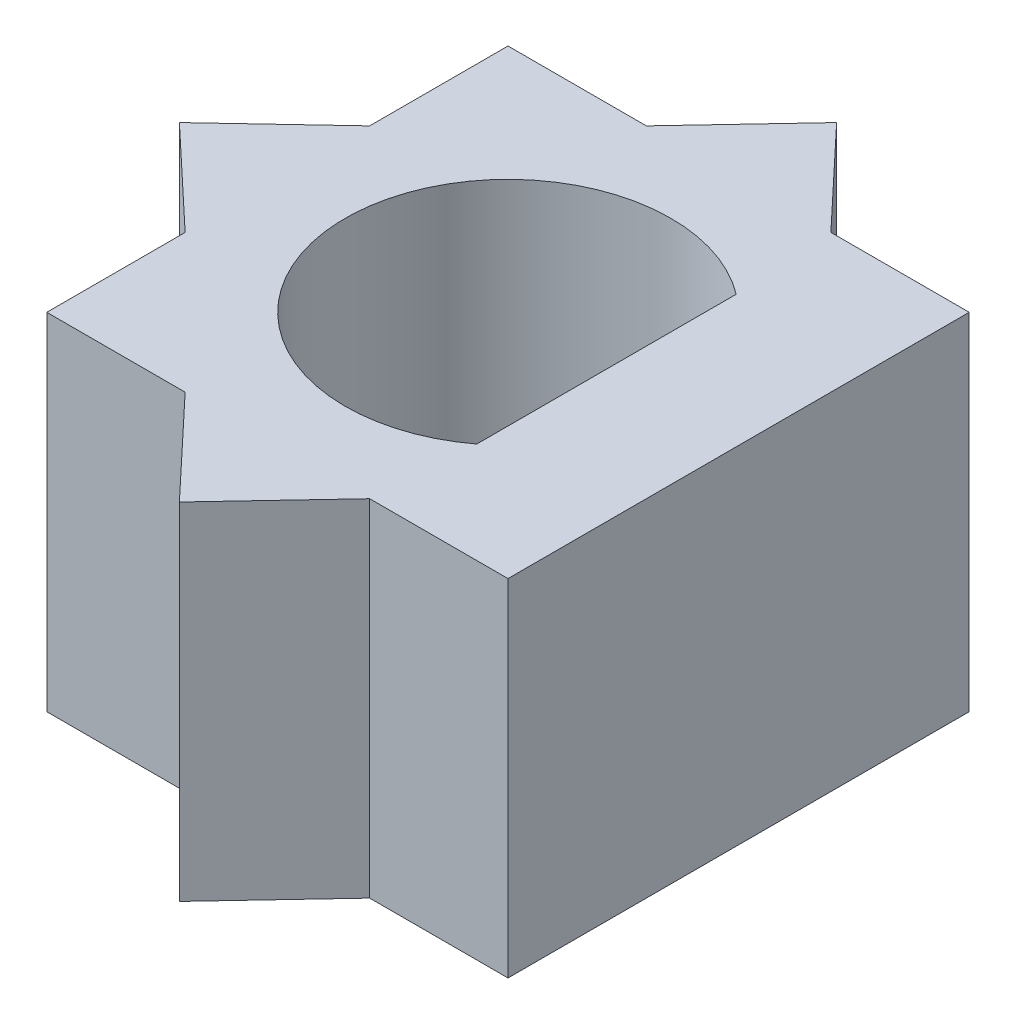
SolidWorks part; units mm, degrees
ref_plane "Plan de face" through (0, 0, 0) normal (0, 0, 1) x (1, 0, 0)
ref_plane "Plan de dessus" through (0, 0, 0) normal (0, 1, 0) x (1, 0, 0)
ref_plane "Plan de droite" through (0, 0, 0) normal (1, 0, 0) x (0, 0, -1)
sketch "Esquisse1" plane through (0, 0, 0) normal (0, 1, 0) x (1, 0, 0)
  line L0 (0, 0) -> (0, 8.5137) construction
  line L1 (-6.9598, 0) -> (8.435, 0) construction
  line L2 (1.1073, -1.1073) -> (9.4238, -9.4238) construction
  line L3 (1.1073, 1.1073) -> (-6.8521, -6.8521) construction
  line L4 (-4, 4) -> (4, 4)
  line L5 (-4, 4) -> (-4, -4)
  line L6 (4, 4) -> (4, -4)
  line L7 (-4, -4) -> (4, -4)
  line L8 (0, 5.7) -> (-1.6, 4)
  line L9 (0, 5.7) -> (1.6, 4)
  line L10 (-5.7, 0) -> (-4, 1.6)
  line L11 (-5.7, 0) -> (-4, -1.6)
  line L12 (0, -5.7) -> (-1.6, -4)
  line L13 (0, -5.7) -> (1.6, -4)
  line L16 (1.7083, 2.25) -> (1.7083, -2.25)
  circle A0 centre (0, 0) radius 2.825
  dimension "D1" = 45
  dimension "5.8" = 5.65
  dimension "D2" = 45
  dimension "D3" = 1.7
  dimension "D4" = 1.7
  dimension "D5" = 2.4
  dimension "D6" = 2.4
  dimension "D7" = 1.7
  dimension "D9" = 2.4
  dimension "D10" = 8
  dimension "D11" = 2.4
  dimension "D12" = 2.4
  dimension "D14" = 2.4
  dimension "D17" = 4.5
extrude "Boss.-Extru.1" add sketch "Esquisse1" along normal blind 6
